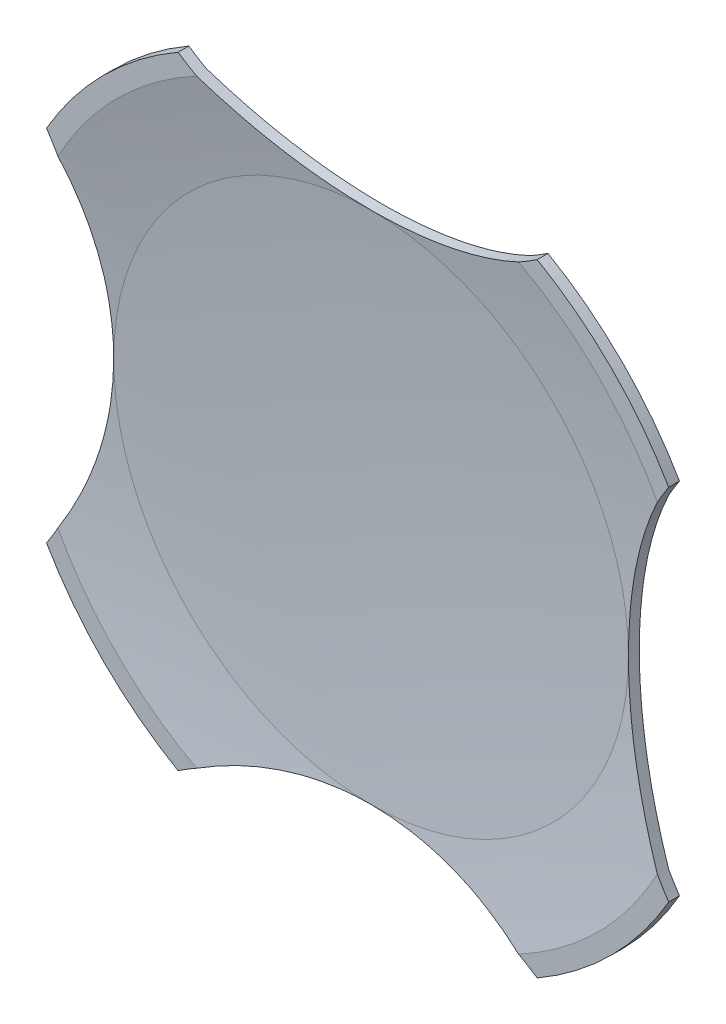
SolidWorks part; units mm, degrees
ref_plane "前视基准面" through (0, 0, 0) normal (0, 0, 1) x (1, 0, 0)
ref_plane "上视基准面" through (0, 0, 0) normal (0, 1, 0) x (1, 0, 0)
ref_plane "右视基准面" through (0, 0, 0) normal (1, 0, 0) x (0, 0, -1)
sketch "草图1" plane through (0, 0, 0) normal (0, 1, 0) x (1, 0, 0)
  line L0 (0, 22.1284) -> (0, -12.8657) construction
  line L1 (4.75, 37.6425) -> (5, 37.6425)
  line L2 (4.7362, 37.4925) -> (5, 37.4925)
  line L3 (0, 38) -> (0, 37.85)
  line L4 (5, 37.6425) -> (5, 37.4925)
  arc A0 (0, 38) -> (3.6, 37.8291) centre (0, 0) cw
  arc A1 (3.6, 37.8291) -> (4.75, 37.6425) centre (0, 12) cw
  arc A2 (0, 37.85) -> (3.5825, 37.6801) centre (0, 0) cw
  arc A3 (3.5825, 37.6801) -> (4.7362, 37.4925) centre (0, 12) cw
  dimension "D1" = 3.6
  dimension "D2" = 38
  dimension "D3" = 12
  dimension "D4" = 4.75
  dimension "D5" = 5
  dimension "D6" = 0.15
revolve "旋转5" add sketch "草图1" angle 360 about L0
sketch "草图2" plane through (0, 0, -37.4925) normal (0, 0, 1) x (1, 0, 0)
  line L0 (0, 8.995) -> (0, -5.8932) construction
  line L2 (-4.6814, 3.5825) -> (4.708, 3.5825) construction
  circle A0 centre (0, 0) radius 3.5825 construction
  circle A1 centre (0, 0) radius 5 construction
  arc A2 (4.3301, -2.5) -> (4.3301, 2.5) centre (0, 0) ccw
  arc A3 (2.5, 4.3301) -> (-2.5, 4.3301) centre (0, 0) ccw
  arc A4 (-2.5, 4.3301) -> (2.5, 4.3301) centre (0, 8.1364) ccw
  arc A5 (4.3301, 2.5) -> (4.3301, -2.5) centre (8.1364, 0) ccw
  arc A6 (-2.5, -4.3301) -> (2.5, -4.3301) centre (0, 0) ccw
  arc A7 (2.5, -4.3301) -> (-2.5, -4.3301) centre (0, -8.1364) ccw
  arc A8 (-4.3301, 2.5) -> (-4.3301, -2.5) centre (0, 0) ccw
  arc A9 (-4.3301, -2.5) -> (-4.3301, 2.5) centre (-8.1364, 0) ccw
  dimension "D1" = 5
extrude "切除-拉伸1" cut sketch "草图2" against normal blind 10
sketch "草图3" plane through (0, 0, -37.4925) normal (0, 0, 1) x (1, 0, 0)
  point P0 (0, 0)
